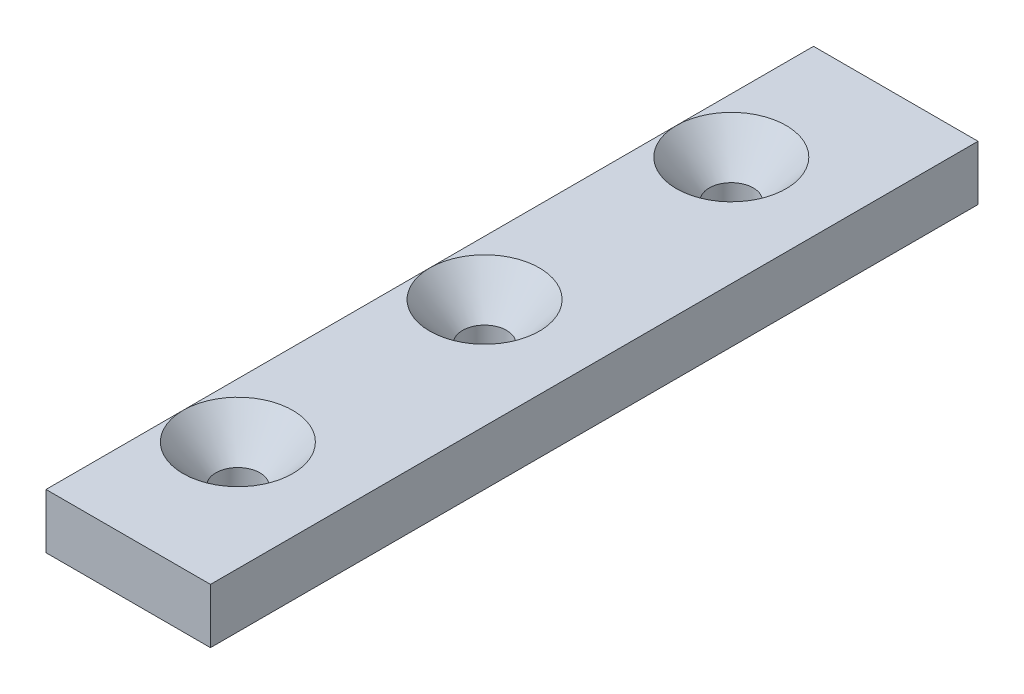
SolidWorks part; units mm, degrees
material "6061 Alloy"
ref_plane "Front Plane" through (0, 0, 0) normal (0, 0, 1) x (1, 0, 0)
ref_plane "Top Plane" through (0, 0, 0) normal (0, 1, 0) x (1, 0, 0)
ref_plane "Right Plane" through (0, 0, 0) normal (1, 0, 0) x (0, 0, -1)
sketch "Sketch1" plane through (0, 0, 0) normal (0, 1, 0) x (1, 0, 0)
  line L1 (0, 0) -> (-19.05, 0)
  line L2 (0, 0) -> (0, 88.9)
  line L3 (0, 88.9) -> (-19.05, 88.9)
  line L4 (-19.05, 0) -> (-19.05, 88.9)
  dimension "D1" = 88.9
  dimension "D2" = 19.05
extrude "Boss-Extrude1" add sketch "Sketch1" along normal blind 6.35
hole_wizard "1/4-20 Tapped Hole1" positions "Sketch2" profile "Sketch3" tap size "1/4-20" standard "ANSI Inch" end condition through all
sketch "Sketch2" plane through (0, 6.35, 0) normal (0, 1, 0) x (1, 0, 0)
  line L0 (-19.05, 0) -> (0, 0) construction
  line L1 (0, 88.9) -> (-19.05, 88.9) construction
  line L2 (-12.7, 0) -> (-12.7, 88.9) construction
  line L4 (-19.05, 88.9) -> (-19.05, 0) construction
  point P0 (-12.7, 15.875)
  point P2 (-12.7, 44.45)
  point P4 (-12.7, 73.025)
  point P18 (0, 0)
  point P19 (0, 0)
  point P20 (0, 0)
  dimension "D1" = 15.875
  dimension "D2" = 15.875
  dimension "D3" = 44.45
  dimension "D4" = 6.35
sketch "Sketch3" plane through (-12.7, 6.35, -15.875) normal (1, 0, 0) x (0, 0, 1)
  line L0 (0, 0) -> (0, 6.35)
  line L1 (0, 6.35) -> (2.5527, 6.35)
  line L2 (2.5527, 6.35) -> (2.5527, 4.3683)
  line L3 (2.5527, 4.3683) -> (6.35, 0)
  line L5 (6.35, 0) -> (0, 0)
  line L6 (-2.5527, 4.3683) -> (-6.35, 0) construction
  line L11 (0, -6.35) -> (0, 107.95) construction
  dimension "Thru Tap Drill Dia." = 5.1054
  dimension "Thru Tap Drill Depth" = 6.35
  dimension "Near C'Sink Dia." = 12.7
  dimension "Near C'Sink Angle" = 82
cosmetic thread "Hole Thread1"
cosmetic thread "Hole Thread2"
cosmetic thread "Hole Thread3"
